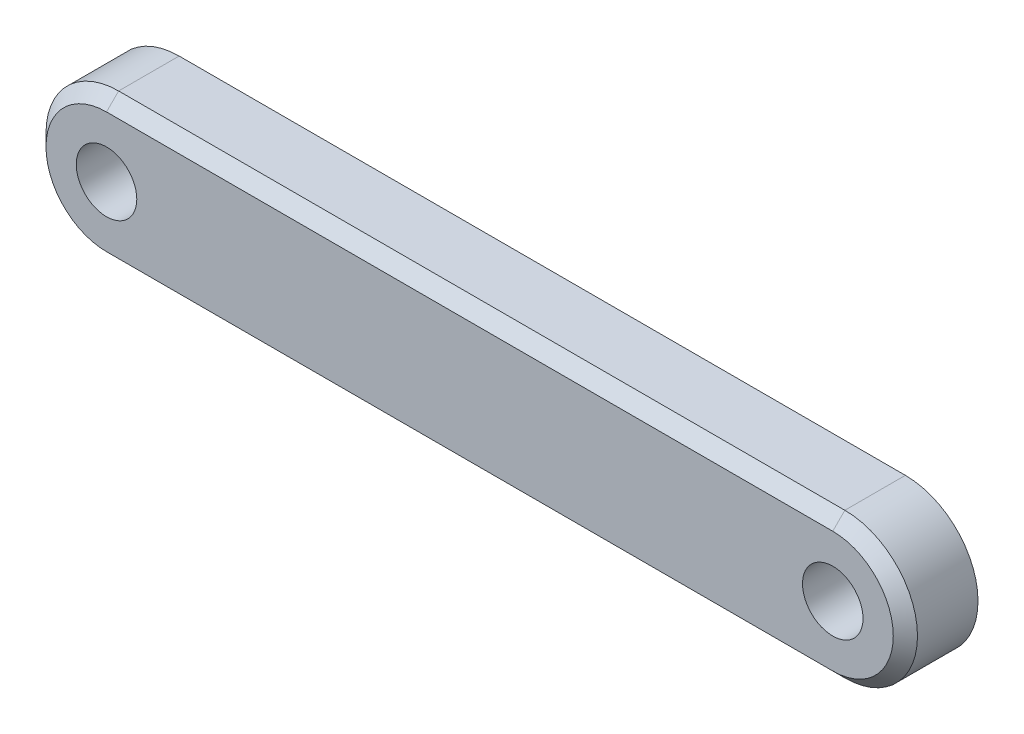
SolidWorks part; units mm, degrees
ref_plane "Alzado" through (0, 0, 0) normal (0, 0, 1) x (1, 0, 0)
ref_plane "Planta" through (0, 0, 0) normal (0, 1, 0) x (1, 0, 0)
ref_plane "Vista lateral" through (0, 0, 0) normal (1, 0, 0) x (0, 0, -1)
sketch "Croquis1" plane through (0, 0, 0) normal (0, 0, 1) x (1, 0, 0)
  line L0 (0, 0) -> (30, 0) construction
  line L1 (0, 3) -> (30, 3)
  line L2 (0, -3) -> (30, -3)
  arc A0 (0, 3) -> (0, -3) centre (0, 0) ccw
  arc A1 (30, -3) -> (30, 3) centre (30, 0) ccw
  circle A2 centre (30, 0) radius 1.25
  circle A3 centre (0, 0) radius 1.25
  point P3 (15, 0)
  dimension "D2" = 3
  dimension "D3" = 2.5
  dimension "D1" = 30
extrude "Saliente-Extruir1" add sketch "Croquis1" along normal blind 3
chamfer "Chaflán1" distance 0.5 angle 45 4 edges at (15, -3, 3) (33, 0, 3) (-3, 0, 3) (15, 3, 3)
